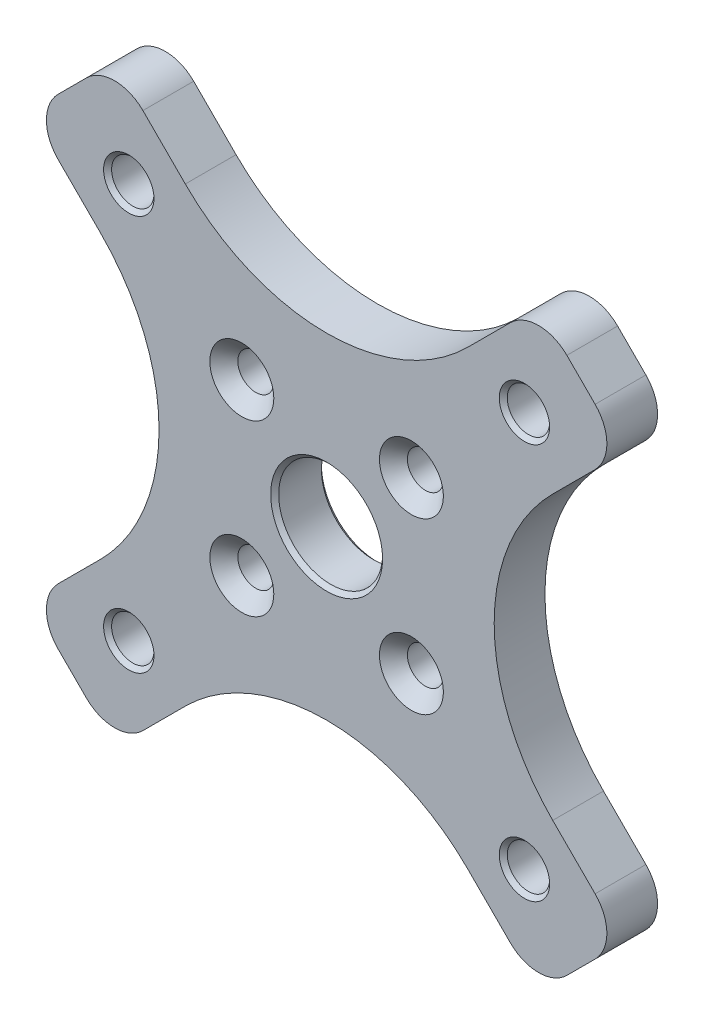
SolidWorks part; units mm, degrees
material "6061 Alloy"
ref_plane "Front Plane" through (0, 0, 0) normal (0, 0, 1) x (1, 0, 0)
ref_plane "Top Plane" through (0, 0, 0) normal (0, 1, 0) x (1, 0, 0)
ref_plane "Right Plane" through (0, 0, 0) normal (1, 0, 0) x (0, 0, -1)
sketch "Sketch1" plane through (0, 0, 0) normal (0, 0, 1) x (1, 0, 0)
  line L0 (0, 10.6066) -> (26.5165, 37.1231)
  line L1 (26.5165, 37.1231) -> (37.1231, 26.5165)
  line L2 (37.1231, 26.5165) -> (10.6066, 0)
  line L3 (10.6066, 0) -> (37.1231, -26.5165)
  line L4 (37.1231, -26.5165) -> (26.5165, -37.1231)
  line L5 (26.5165, -37.1231) -> (0, -10.6066)
  line L6 (0, -10.6066) -> (-26.5165, -37.1231)
  line L7 (-26.5165, -37.1231) -> (-37.1231, -26.5165)
  line L8 (-37.1231, -26.5165) -> (-10.6066, 0)
  line L9 (-10.6066, 0) -> (-37.1231, 26.5165)
  line L10 (-37.1231, 26.5165) -> (-26.5165, 37.1231)
  line L11 (-26.5165, 37.1231) -> (0, 10.6066)
  line L12 (-31.8198, -31.8198) -> (31.8198, 31.8198) construction
  line L13 (-31.8198, 31.8198) -> (31.8198, -31.8198) construction
  line L14 (0, 0) -> (58.3953, 0) construction
  circle A0 centre (0, 0) radius 6.5
  dimension "D1" = 13
  dimension "D5" = 63.6396
  dimension "D2" = 45
  dimension "D3" = 15
  dimension "D4" = 90
extrude "1/4 in Sheet Metal" add sketch "Sketch1" along normal mid plane 6.35
hole_wizard "M4 Clearance Hole1" positions "Sketch5" profile "Sketch6" hole size "M4" standard "ANSI Metric" end condition up to next
sketch "Sketch5" plane through (0, 0, 3.175) normal (0, 0, 1) x (1, 0, 0)
  line L0 (-31.8198, -31.8198) -> (31.8198, 31.8198) construction
  line L1 (-37.1231, -26.5165) -> (-26.5165, -37.1231) construction
  line L2 (37.1231, 26.5165) -> (26.5165, 37.1231) construction
  line L3 (-31.8198, 31.8198) -> (31.8198, -31.8198) construction
  line L4 (-26.5165, 37.1231) -> (-37.1231, 26.5165) construction
  line L5 (26.5165, -37.1231) -> (37.1231, -26.5165) construction
  line L7 (-10.6066, 10.6066) -> (10.6066, 10.6066) construction
  line L8 (10.6066, 10.6066) -> (10.6066, -10.6066) construction
  line L9 (10.6066, -10.6066) -> (-10.6066, -10.6066) construction
  line L10 (-10.6066, -10.6066) -> (-10.6066, 10.6066) construction
  circle A0 centre (0, 0) radius 15 construction
  point P0 (-10.6066, 10.6066)
  point P2 (10.6066, 10.6066)
  point P4 (10.6066, -10.6066)
  point P6 (-10.6066, -10.6066)
  dimension "D1" = 30
sketch "Sketch6" plane through (-10.6066, 10.6066, 3.175) normal (1, 0, 0) x (0, -1, 0)
  line L0 (0, 0) -> (0, 6.35)
  line L1 (0, 6.35) -> (2.25, 6.35)
  line L2 (2.25, 6.35) -> (2.25, 1.75)
  line L3 (2.25, 1.75) -> (4, 0)
  line L5 (4, 0) -> (0, 0)
  line L6 (-2.25, 1.75) -> (-4, 0) construction
  line L11 (0, -6.35) -> (0, 107.95) construction
  dimension "Thru Hole Dia." = 4.5
  dimension "Thru Hole Depth" = 6.35
  dimension "Near C'Sink Dia." = 8
  dimension "Near C'Sink Angle" = 90
hole_wizard "M5 Clearance Hole1" positions "Sketch7" profile "Sketch8" hole size "M5" standard "ANSI Metric" end condition up to next
sketch "Sketch7" plane through (0, 0, -3.175) normal (0, 0, -1) x (-1, 0, 0)
  line L0 (-31.8198, -31.8198) -> (31.8198, 31.8198) construction
  line L1 (-26.5165, -37.1231) -> (-37.1231, -26.5165) construction
  line L2 (26.5165, 37.1231) -> (37.1231, 26.5165) construction
  line L4 (-31.8198, 31.8198) -> (31.8198, -31.8198) construction
  line L5 (-37.1231, 26.5165) -> (-26.5165, 37.1231) construction
  line L6 (37.1231, -26.5165) -> (26.5165, -37.1231) construction
  line L8 (-24.7487, 24.7487) -> (24.7487, 24.7487) construction
  line L9 (24.7487, 24.7487) -> (24.7487, -24.7487) construction
  line L10 (24.7487, -24.7487) -> (-24.7487, -24.7487) construction
  line L11 (-24.7487, -24.7487) -> (-24.7487, 24.7487) construction
  circle A0 centre (0, 0) radius 35 construction
  point P0 (-24.7487, 24.7487)
  point P2 (24.7487, 24.7487)
  point P4 (24.7487, -24.7487)
  point P6 (-24.7487, -24.7487)
  dimension "D1" = 70
sketch "Sketch8" plane through (24.7487, 24.7487, -3.175) normal (1, 0, 0) x (0, 1, 0)
  line L0 (0, 0) -> (0, 6.35)
  line L1 (0, 6.35) -> (2.65, 6.35)
  line L2 (2.65, 6.35) -> (2.65, 0)
  line L5 (2.65, 0) -> (0, 0)
  line L11 (0, -6.35) -> (0, 107.95) construction
  dimension "Thru Hole Dia." = 5.3
  dimension "Thru Hole Depth" = 6.35
fillet "25 mm Fillet" radius 25 4 edges at (-10.6066, 0, 0) (0, -10.6066, 0) (10.6066, 0, 0) (0, 10.6066, 0)
fillet "5 mm Fillet" radius 5 8 edges at (26.5165, -37.1231, 0) (37.1231, -26.5165, 0) (-26.5165, -37.1231, 0) (-37.1231, -26.5165, 0) (-37.1231, 26.5165, 0) (-26.5165, 37.1231, 0) (37.1231, 26.5165, 0) (26.5165, 37.1231, 0)
chamfer "0.50 mm Chamfer" distance 0.5 angle 45 10 edges at (6.5, 0, -3.175) (6.5, 0, 3.175) (27.3987, -24.7487, 3.175) (22.0987, -24.7487, -3.175) (-22.0987, -24.7487, 3.175) (-27.3987, -24.7487, -3.175) (27.3987, 24.7487, 3.175) (22.0987, 24.7487, -3.175) (-22.0987, 24.7487, 3.175) (-27.3987, 24.7487, -3.175)
